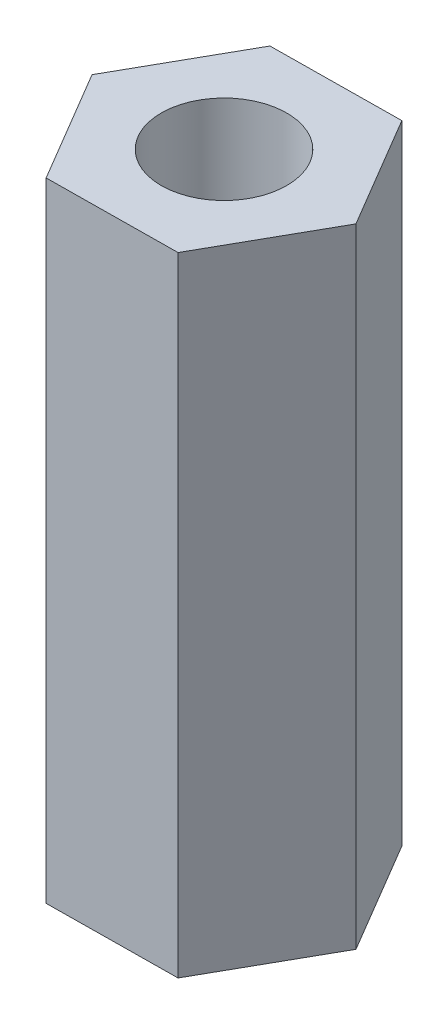
SolidWorks part; units mm, degrees
ref_plane "Front Plane" through (0, 0, 0) normal (0, 0, 1) x (1, 0, 0)
ref_plane "Top Plane" through (0, 0, 0) normal (0, 1, 0) x (1, 0, 0)
ref_plane "Right Plane" through (0, 0, 0) normal (1, 0, 0) x (0, 0, -1)
sketch "Sketch1" plane through (0, 0, 0) normal (0, 1, 0) x (1, 0, 0)
  line L0 (1.5307, 2.7161) -> (-1.5868, 2.6836)
  line L1 (-1.5868, 2.6836) -> (-3.1175, -0.0324)
  line L2 (-3.1175, -0.0324) -> (-1.5307, -2.7161)
  line L3 (-1.5307, -2.7161) -> (1.5868, -2.6836)
  line L4 (1.5868, -2.6836) -> (3.1175, 0.0324)
  line L5 (3.1175, 0.0324) -> (1.5307, 2.7161)
  circle A0 centre (0, 0) radius 1.5
extrude "Boss-Extrude1" add sketch "Sketch1" along normal blind 15
